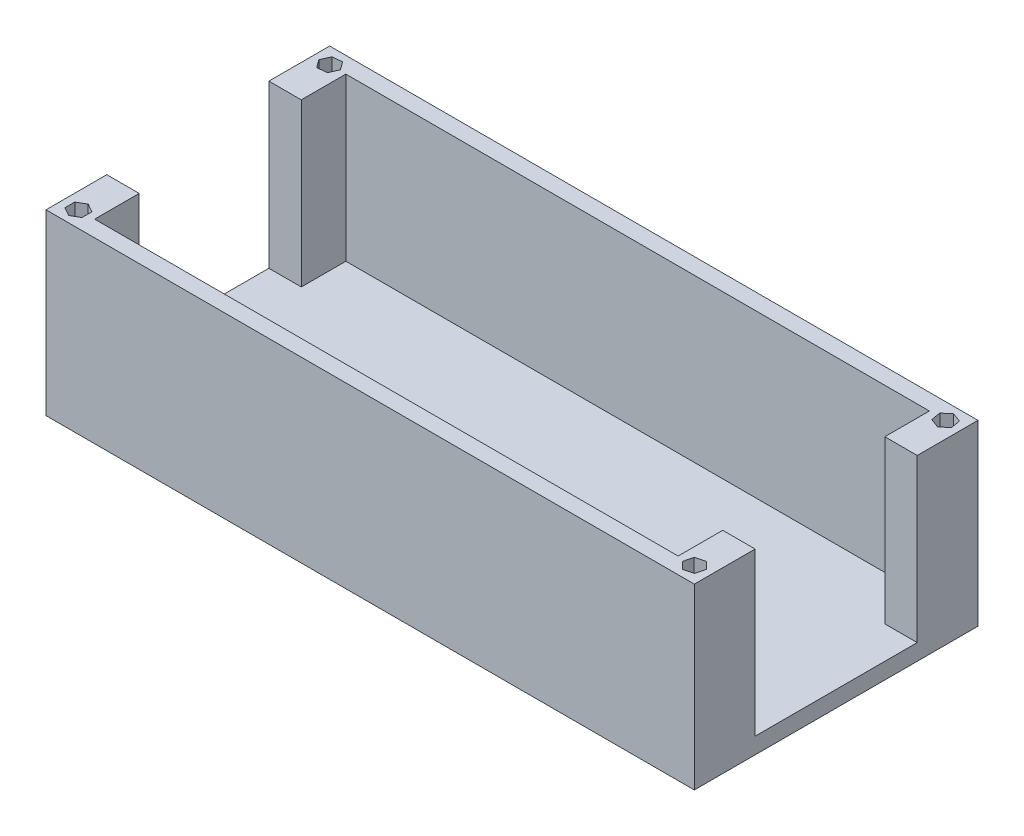
SolidWorks part; units mm, degrees
ref_plane "Front Plane" through (0, 0, 0) normal (0, 0, 1) x (1, 0, 0)
ref_plane "Top Plane" through (0, 0, 0) normal (0, 1, 0) x (1, 0, 0)
ref_plane "Right Plane" through (0, 0, 0) normal (1, 0, 0) x (0, 0, -1)
sketch "Sketch1" plane through (0, 0, 0) normal (0, 1, 0) x (1, 0, 0)
  line L1 (0, 0) -> (80, 0)
  line L2 (0, 0) -> (0, -35)
  line L3 (0, -35) -> (80, -35)
  line L4 (80, 0) -> (80, -35)
  dimension "D1" = 80
  dimension "D2" = 35
extrude "Boss-Extrude1" add sketch "Sketch1" along normal blind 2
sketch "Sketch2" plane through (0, 2, 0) normal (0, 1, 0) x (1, 0, 0)
  line L0 (0, -35) -> (80, -35) construction
  line L1 (0, 0) -> (80, 0)
  line L2 (0, 0) -> (0, -7.5)
  line L3 (0, -35) -> (80, -35)
  line L4 (80, 0) -> (80, -7.5)
  line L5 (80, -35) -> (80, 0) construction
  line L6 (4, -2) -> (76, -2)
  line L7 (4, -2) -> (4, -7.5)
  line L8 (4, -33) -> (76, -33)
  line L9 (76, -2) -> (76, -7.5)
  line L10 (0, -27.5) -> (0, -35)
  line L11 (0, -7.5) -> (4, -7.5)
  line L13 (0, -27.5) -> (4, -27.5)
  line L15 (76, -7.5) -> (80, -7.5)
  line L17 (76, -27.5) -> (80, -27.5)
  line L19 (4, -27.5) -> (4, -33)
  line L20 (76, -27.5) -> (76, -33)
  line L21 (80, -27.5) -> (80, -35)
  dimension "D1" = 2
  dimension "D2" = 2
  dimension "D3" = 4
  dimension "D4" = 4
  dimension "D5" = 20
extrude "Boss-Extrude2" add sketch "Sketch2" along normal blind 20
sketch "Sketch3" plane through (0, 22, 0) normal (0, 1, 0) x (1, 0, 0)
  line L0 (80, -27.5) -> (80, -7.5) construction
  line L1 (2, -2) -> (78, -2) construction
  line L2 (2, -2) -> (2, -33) construction
  line L3 (2, -33) -> (78, -33) construction
  line L4 (78, -2) -> (78, -33) construction
  line L5 (0, -35) -> (80, -35) construction
  line L6 (80, 0) -> (0, 0) construction
  line L7 (0, -7.5) -> (0, -27.5) construction
  line L9 (2.4906, -0.8912) -> (1.2851, -1.0208)
  line L10 (1.2851, -1.0208) -> (0.7945, -2.1295)
  line L11 (0.7945, -2.1295) -> (1.5094, -3.1088)
  line L12 (1.5094, -3.1088) -> (2.7149, -2.9792)
  line L13 (2.7149, -2.9792) -> (3.2055, -1.8705)
  line L14 (3.2055, -1.8705) -> (2.4906, -0.8912)
  line L15 (2, -31.7876) -> (0.95, -32.3938)
  line L16 (0.95, -32.3938) -> (0.95, -33.6062)
  line L17 (0.95, -33.6062) -> (2, -34.2124)
  line L18 (2, -34.2124) -> (3.05, -33.6062)
  line L19 (3.05, -33.6062) -> (3.05, -32.3938)
  line L20 (3.05, -32.3938) -> (2, -31.7876)
  line L21 (78.304, -31.8263) -> (77.1356, -32.1498)
  line L22 (77.1356, -32.1498) -> (76.8315, -33.3235)
  line L23 (76.8315, -33.3235) -> (77.696, -34.1737)
  line L24 (77.696, -34.1737) -> (78.8644, -33.8502)
  line L25 (78.8644, -33.8502) -> (79.1685, -32.6765)
  line L26 (79.1685, -32.6765) -> (78.304, -31.8263)
  line L27 (78.9324, -1.2251) -> (77.7951, -0.805)
  line L28 (77.7951, -0.805) -> (76.8627, -1.58)
  line L29 (76.8627, -1.58) -> (77.0676, -2.7749)
  line L30 (77.0676, -2.7749) -> (78.2049, -3.195)
  line L31 (78.2049, -3.195) -> (79.1373, -2.42)
  line L32 (79.1373, -2.42) -> (78.9324, -1.2251)
  circle A0 centre (2, -2) radius 1.05 construction
  circle A1 centre (2, -33) radius 1.05 construction
  circle A2 centre (78, -33) radius 1.05 construction
  circle A3 centre (78, -2) radius 1.05 construction
  dimension "D5" = 2.1
  dimension "D1" = 2
  dimension "D2" = 2
  dimension "D3" = 2
  dimension "D4" = 2
extrude "Cut-Extrude1" cut sketch "Sketch3" against normal blind 2.3
